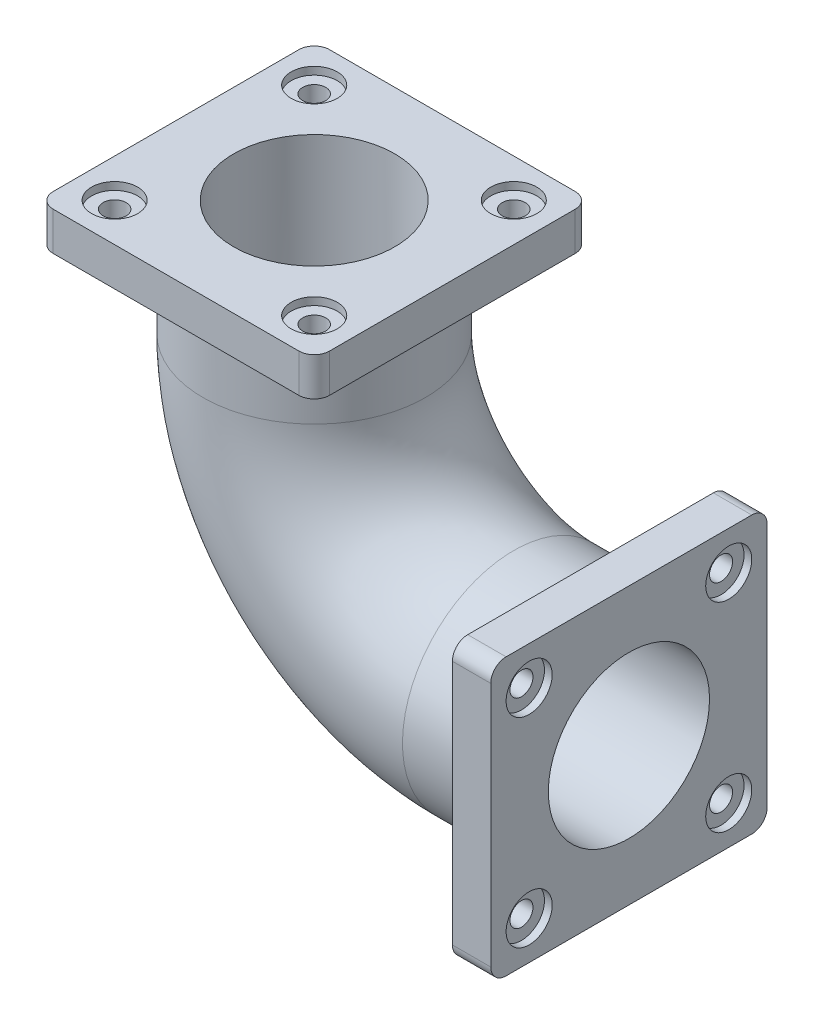
SolidWorks part; units mm, degrees
ref_plane "Front Plane" through (0, 0, 0) normal (0, 0, 1) x (1, 0, 0)
ref_plane "Top Plane" through (0, 0, 0) normal (0, 1, 0) x (1, 0, 0)
ref_plane "Right Plane" through (0, 0, 0) normal (1, 0, 0) x (0, 0, -1)
sketch "Sketch1" plane through (0, 0, 0) normal (0, 0, 1) x (1, 0, 0)
  line L0 (0, 0) -> (-150, 0)
  line L1 (-410, 260) -> (-410, 410)
  arc A0 (-150, 0) -> (-410, 260) centre (-150, 260) cw
  dimension "D3" = 260
  dimension "D1" = 150
  dimension "D2" = 150
ref_plane "Plane2" through (0, 410, 0) normal (0, 1, 0) x (1, 0, 0)
sketch "Sketch3" plane through (0, 410, 0) normal (0, 1, 0) x (1, 0, 0)
  line L0 (-410, 0) -> (-150, 0) construction
  circle A0 centre (-410, 0) radius 145
  circle A1 centre (-410, 0) radius 105
  point P5 (0, 0)
  dimension "D1" = 290
  dimension "D2" = 210
sweep "Sweep1" add profiles "Sketch3" path "Sketch1"
sketch "Sketch5" plane through (0, 410, 0) normal (0, 1, 0) x (1, 0, 0)
  line L1 (-230, 180) -> (-590, 180)
  line L2 (-230, 180) -> (-230, -180)
  line L3 (-230, -180) -> (-590, -180)
  line L4 (-590, 180) -> (-590, -180)
  line L5 (-230, 180) -> (-590, -180) construction
  line L6 (-230, -180) -> (-590, 180) construction
  point P0 (-410, 0)
  dimension "D1" = 360
  dimension "D2" = 360
extrude "Boss-Extrude1" add sketch "Sketch5" against normal blind 50
sketch "Sketch6" plane through (0, 410, 0) normal (0, 1, 0) x (1, 0, 0)
  line L0 (-410, 180) -> (-410, -180) construction
  line L1 (-230, 180) -> (-590, 180) construction
  line L2 (-590, -180) -> (-230, -180) construction
  line L3 (-590, 0) -> (-230, 0) construction
  line L4 (-590, 180) -> (-590, -180) construction
  line L5 (-230, -180) -> (-230, 180) construction
  circle A0 centre (-410, 0) radius 105
  dimension "D1" = 210
extrude "Cut-Extrude1" cut sketch "Sketch6" against normal blind 50
sketch "Sketch7" plane through (0, 410, 0) normal (0, 1, 0) x (1, 0, 0)
  line L0 (-230, 180) -> (-590, 180) construction
  line L1 (-590, 180) -> (-590, -180) construction
  line L2 (-410, 180) -> (-410, -180) construction
  line L3 (-590, -180) -> (-230, -180) construction
  line L4 (-590, 0) -> (-230, 0) construction
  line L5 (-230, -180) -> (-230, 180) construction
  circle A0 centre (-540, 130) radius 30
  circle A1 centre (-540, 130) radius 15
  circle A2 centre (-280, 130) radius 15
  circle A3 centre (-280, 130) radius 30
  circle A4 centre (-280, -130) radius 15
  circle A5 centre (-280, -130) radius 30
  circle A6 centre (-540, -130) radius 15
  circle A7 centre (-540, -130) radius 30
  dimension "D1" = 60
  dimension "D4" = 30
  dimension "D2" = 50
  dimension "D3" = 50
fillet "Fillet1" radius 20 4 edges at (-590, 385, 180) (-230, 385, 180) (-230, 385, -180) (-590, 385, -180)
ref_plane "Plane3" through (-205, 205, 0) normal (-0.7071, 0.7071, 0) x (0.7071, 0.7071, 0)
extrude "Cut-Extrude4" cut sketch "Sketch7" against normal blind 50 contours A1 | A4 | A2 | A6
sketch "Sketch9" plane through (0, 410, 0) normal (0, 1, 0) x (1, 0, 0)
  circle A0 centre (-540, -130) radius 30
  circle A1 centre (-280, -130) radius 30
  circle A2 centre (-540, 130) radius 30
  circle A3 centre (-280, 130) radius 30
extrude "Cut-Extrude5" cut sketch "Sketch9" against normal blind 10
mirror "Mirror3" about plane through (-205, 205, 0) normal (-0.7071, 0.7071, 0) of "Boss-Extrude1", "Cut-Extrude1", "Fillet1", "Cut-Extrude5", "Cut-Extrude4"
